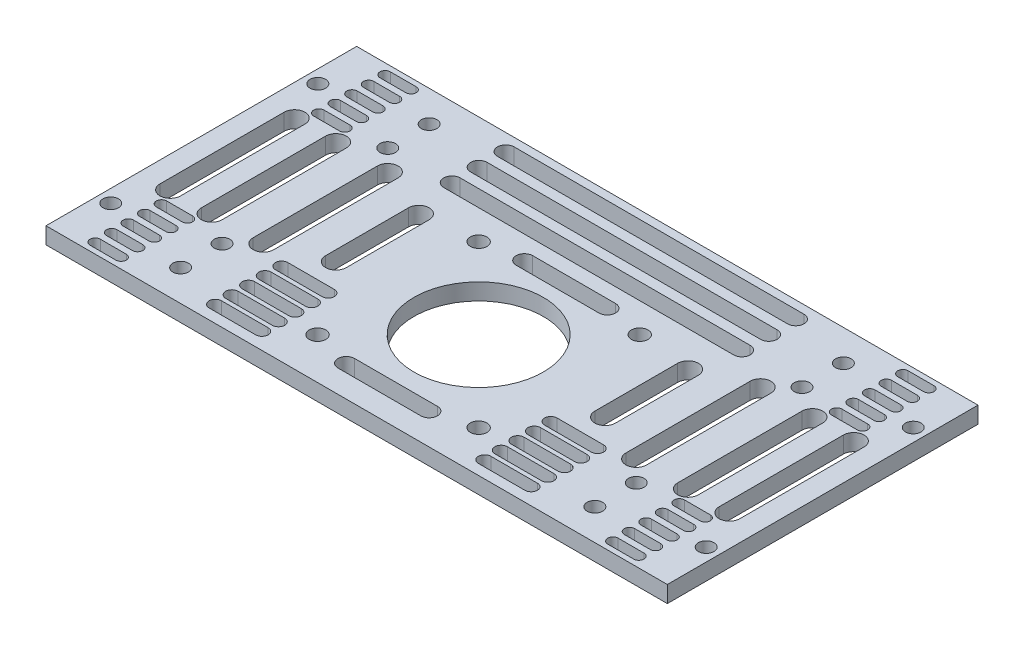
SolidWorks part; units mm, degrees
ref_plane "前视基准面" through (0, 0, 0) normal (0, 0, 1) x (1, 0, 0)
ref_plane "上视基准面" through (0, 0, 0) normal (0, 1, 0) x (1, 0, 0)
ref_plane "右视基准面" through (0, 0, 0) normal (1, 0, 0) x (0, 0, -1)
other "Configuration Table"
sketch "草图1" plane through (0, 0, 0) normal (0, 1, 0) x (1, 0, 0)
  line L0 (0, 30) -> (0, -30) construction
  line L1 (-60, 30) -> (60, 30)
  line L2 (-60, 30) -> (-60, -30)
  line L3 (-60, -30) -> (60, -30)
  line L4 (60, 30) -> (60, -30)
  line L6 (-60, 0) -> (60, 0) construction
  dimension "D1" = 60
  dimension "D2" = 120
extrude "凸台-拉伸1" add sketch "草图1" along normal blind 3.2
sketch "草图2" plane through (0, 3.2, 0) normal (0, 1, 0) x (1, 0, 0)
  line L0 (0, 0) -> (0, -30) construction
  line L1 (-60, -30) -> (60, -30) construction
  line L2 (0, 0) -> (0, 30) construction
  line L3 (60, 30) -> (-60, 30) construction
  line L4 (-15.5563, -22) -> (15.5563, -22) construction
  line L5 (0, -6.4437) -> (0, -22) construction
  line L6 (-60, 0) -> (60, 0) construction
  line L7 (-60, 30) -> (-60, -30) construction
  line L8 (60, -30) -> (60, 30) construction
  line L9 (-57.5, 30) -> (-57.5, -30) construction
  line L10 (-60, -20) -> (60, -20) construction
  line L11 (-60, 20) -> (60, 20) construction
  circle A0 centre (0, -6.4437) radius 12.5
  circle A1 centre (15.5563, -22) radius 1.6
  circle A2 centre (15.5563, 9.1127) radius 1.6
  circle A3 centre (-15.5563, 9.1127) radius 1.6
  circle A4 centre (-15.5563, -22) radius 1.6
  circle A5 centre (-57.5, 20) radius 1.5
  circle A6 centre (-57.5, -20) radius 1.5
  circle A7 centre (57.5, -20) radius 1.5
  circle A8 centre (57.5, 20) radius 1.5
  circle A9 centre (-40, -24) radius 1.5
  circle A10 centre (-40, -16) radius 1.5
  circle A11 centre (-40, 24) radius 1.5
  circle A12 centre (-40, 16) radius 1.5
  circle A13 centre (40, -24) radius 1.5
  circle A14 centre (40, -16) radius 1.5
  circle A15 centre (40, 24) radius 1.5
  circle A16 centre (40, 16) radius 1.5
  point P43 (-77.007, -22.6558)
  point P44 (-45.3884, -20.927)
  point P45 (-45.7748, -18.8737)
  dimension "D1" = 25
  dimension "D2" = 3.2
  dimension "D6" = 3
  dimension "D7" = 3
  dimension "D12" = 3
  dimension "D3" = 22
  dimension "D5" = 8
  dimension "D8" = 20
  dimension "D9" = 20
  dimension "D10" = 2.5
  dimension "D11" = 20
  dimension "D13" = 20
  dimension "D14" = 4
  dimension "D4" = 4
extrude "切除-拉伸1" cut sketch "草图2" against normal up to surface (3.2 mm away) up to face at (0, 0, 0)
sketch "草图3" plane through (0, 3.2, 0) normal (0, 1, 0) x (1, 0, 0)
  line L0 (0, 30) -> (0, -30) construction
  line L1 (60, 30) -> (-60, 30) construction
  line L2 (-60, -30) -> (60, -30) construction
  line L3 (-60, 0) -> (60, 0) construction
  line L4 (-60, 30) -> (-60, -30) construction
  line L5 (60, -30) -> (60, 30) construction
  line L6 (-28, 26.8) -> (28, 26.8) construction
  line L7 (-28, 28.4) -> (28, 28.4)
  line L8 (-28, 25.2) -> (28, 25.2)
  line L9 (-28, 21.6) -> (28, 21.6) construction
  line L10 (-28, 23.2) -> (28, 23.2)
  line L11 (-28, 20) -> (28, 20)
  line L12 (-28, 16.4) -> (28, 16.4) construction
  line L13 (-28, 18) -> (28, 18)
  line L14 (-28, 14.8) -> (28, 14.8)
  line L15 (-8, 10.4) -> (8, 10.4) construction
  line L16 (-8, 12) -> (8, 12)
  line L17 (-8, 8.8) -> (8, 8.8)
  line L18 (-8, -24) -> (8, -24) construction
  line L19 (-8, -22.4) -> (8, -22.4)
  line L20 (-8, -25.6) -> (8, -25.6)
  line L21 (-54, 12) -> (-54, -12) construction
  line L22 (-52, 12) -> (-52, -12)
  line L23 (-56, 12) -> (-56, -12)
  line L24 (-46, 12) -> (-46, -12) construction
  line L25 (-44, 12) -> (-44, -12)
  line L26 (-48, 12) -> (-48, -12)
  line L27 (-36, 12) -> (-36, -12) construction
  line L30 (-34, 12) -> (-34, -12)
  line L31 (-38, 12) -> (-38, -12)
  line L32 (54, 12) -> (54, -12) construction
  line L35 (-26, 8) -> (-26, -8) construction
  line L36 (-24, 8) -> (-24, -8)
  line L37 (-28, 8) -> (-28, -8)
  line L38 (52, 12) -> (52, -12)
  line L39 (56, 12) -> (56, -12)
  line L40 (46, 12) -> (46, -12) construction
  line L41 (44, 12) -> (44, -12)
  line L42 (48, 12) -> (48, -12)
  line L43 (36, 12) -> (36, -12) construction
  line L44 (34, 12) -> (34, -12)
  line L45 (38, 12) -> (38, -12)
  line L46 (26, 8) -> (26, -8) construction
  line L47 (24, 8) -> (24, -8)
  line L48 (28, 8) -> (28, -8)
  line L49 (-26, 8) -> (-26, -30) construction
  line L50 (-30.5, -17.2) -> (-21.5, -17.2) construction
  line L51 (-30.5, -16) -> (-21.5, -16)
  line L52 (-30.5, -18.4) -> (-21.5, -18.4)
  line L53 (-30.5, -20.4) -> (-21.5, -20.4) construction
  line L54 (-30.5, -19.2) -> (-21.5, -19.2)
  line L55 (-30.5, -21.6) -> (-21.5, -21.6)
  line L56 (-30.5, -23.6) -> (-21.5, -23.6) construction
  line L57 (-30.5, -22.4) -> (-21.5, -22.4)
  line L58 (-30.5, -24.8) -> (-21.5, -24.8)
  line L59 (-30.5, -26.8) -> (-21.5, -26.8) construction
  line L60 (-30.5, -25.6) -> (-21.5, -25.6)
  line L61 (-30.5, -28) -> (-21.5, -28)
  line L62 (-52, -12) -> (-48, -12) construction
  line L63 (-50, -12) -> (-50, -30) construction
  line L64 (-52.5, -15.2) -> (-47.5, -15.2) construction
  line L67 (-52.5, -18.4) -> (-47.5, -18.4) construction
  line L70 (-52.5, -24.8) -> (-47.5, -24.8) construction
  line L73 (-52.5, -23.8) -> (-47.5, -23.8)
  line L76 (-52.5, -28) -> (-47.5, -28) construction
  line L77 (-52.5, -27) -> (-47.5, -27)
  line L78 (-52.5, -29) -> (-47.5, -29)
  line L79 (-52.5, -17.4) -> (-47.5, -17.4)
  line L80 (-52.5, -19.4) -> (-47.5, -19.4)
  line L81 (-30.5, -14) -> (-21.5, -14) construction
  line L82 (-30.5, -12.8) -> (-21.5, -12.8)
  line L83 (-30.5, -15.2) -> (-21.5, -15.2)
  line L84 (-52.5, -25.8) -> (-47.5, -25.8)
  line L85 (-52.5, -21.6) -> (-47.5, -21.6) construction
  line L86 (-52.5, -20.6) -> (-47.5, -20.6)
  line L87 (-52.5, -22.6) -> (-47.5, -22.6)
  line L88 (-52.5, -14.2) -> (-47.5, -14.2)
  line L89 (-52.5, -16.2) -> (-47.5, -16.2)
  line L90 (52.5, -15.2) -> (47.5, -15.2) construction
  line L91 (52.5, -14.2) -> (47.5, -14.2)
  line L92 (52.5, -16.2) -> (47.5, -16.2)
  line L93 (52.5, -18.4) -> (47.5, -18.4) construction
  line L94 (52.5, -17.4) -> (47.5, -17.4)
  line L95 (52.5, -19.4) -> (47.5, -19.4)
  line L96 (52.5, -21.6) -> (47.5, -21.6) construction
  line L97 (52.5, -20.6) -> (47.5, -20.6)
  line L98 (52.5, -22.6) -> (47.5, -22.6)
  line L99 (52.5, -24.8) -> (47.5, -24.8) construction
  line L100 (52.5, -23.8) -> (47.5, -23.8)
  line L101 (52.5, -25.8) -> (47.5, -25.8)
  line L102 (52.5, -28) -> (47.5, -28) construction
  line L103 (52.5, -27) -> (47.5, -27)
  line L104 (52.5, -29) -> (47.5, -29)
  line L105 (30.5, -26.8) -> (21.5, -26.8) construction
  line L106 (30.5, -25.6) -> (21.5, -25.6)
  line L107 (30.5, -28) -> (21.5, -28)
  line L108 (30.5, -23.6) -> (21.5, -23.6) construction
  line L109 (30.5, -22.4) -> (21.5, -22.4)
  line L110 (30.5, -24.8) -> (21.5, -24.8)
  line L111 (30.5, -20.4) -> (21.5, -20.4) construction
  line L112 (30.5, -19.2) -> (21.5, -19.2)
  line L113 (30.5, -21.6) -> (21.5, -21.6)
  line L114 (30.5, -17.2) -> (21.5, -17.2) construction
  line L115 (30.5, -16) -> (21.5, -16)
  line L116 (30.5, -18.4) -> (21.5, -18.4)
  line L117 (30.5, -14) -> (21.5, -14) construction
  line L118 (30.5, -12.8) -> (21.5, -12.8)
  line L119 (30.5, -15.2) -> (21.5, -15.2)
  line L120 (-52.5, 15.2) -> (-47.5, 15.2) construction
  line L121 (-52.5, 14.2) -> (-47.5, 14.2)
  line L122 (-52.5, 16.2) -> (-47.5, 16.2)
  line L123 (-52.5, 18.4) -> (-47.5, 18.4) construction
  line L124 (-52.5, 17.4) -> (-47.5, 17.4)
  line L125 (-52.5, 19.4) -> (-47.5, 19.4)
  line L126 (-52.5, 21.6) -> (-47.5, 21.6) construction
  line L127 (-52.5, 20.6) -> (-47.5, 20.6)
  line L128 (-52.5, 22.6) -> (-47.5, 22.6)
  line L129 (-52.5, 24.8) -> (-47.5, 24.8) construction
  line L130 (-52.5, 23.8) -> (-47.5, 23.8)
  line L131 (-52.5, 25.8) -> (-47.5, 25.8)
  line L132 (-52.5, 28) -> (-47.5, 28) construction
  line L133 (-52.5, 27) -> (-47.5, 27)
  line L134 (-52.5, 29) -> (-47.5, 29)
  line L135 (52.5, 15.2) -> (47.5, 15.2) construction
  line L136 (52.5, 14.2) -> (47.5, 14.2)
  line L137 (52.5, 16.2) -> (47.5, 16.2)
  line L138 (52.5, 18.4) -> (47.5, 18.4) construction
  line L139 (52.5, 17.4) -> (47.5, 17.4)
  line L140 (52.5, 19.4) -> (47.5, 19.4)
  line L141 (52.5, 21.6) -> (47.5, 21.6) construction
  line L142 (52.5, 20.6) -> (47.5, 20.6)
  line L143 (52.5, 22.6) -> (47.5, 22.6)
  line L144 (52.5, 24.8) -> (47.5, 24.8) construction
  line L145 (52.5, 23.8) -> (47.5, 23.8)
  line L146 (52.5, 25.8) -> (47.5, 25.8)
  line L147 (52.5, 28) -> (47.5, 28) construction
  line L148 (52.5, 27) -> (47.5, 27)
  line L149 (52.5, 29) -> (47.5, 29)
  arc A0 (-28, 28.4) -> (-28, 25.2) centre (-28, 26.8) ccw
  arc A1 (28, 25.2) -> (28, 28.4) centre (28, 26.8) ccw
  arc A2 (-28, 23.2) -> (-28, 20) centre (-28, 21.6) ccw
  arc A3 (28, 20) -> (28, 23.2) centre (28, 21.6) ccw
  arc A4 (-28, 18) -> (-28, 14.8) centre (-28, 16.4) ccw
  arc A5 (28, 14.8) -> (28, 18) centre (28, 16.4) ccw
  arc A6 (-8, 12) -> (-8, 8.8) centre (-8, 10.4) ccw
  arc A7 (8, 8.8) -> (8, 12) centre (8, 10.4) ccw
  arc A8 (-8, -22.4) -> (-8, -25.6) centre (-8, -24) ccw
  arc A9 (8, -25.6) -> (8, -22.4) centre (8, -24) ccw
  arc A10 (-52, 12) -> (-56, 12) centre (-54, 12) ccw
  arc A11 (-56, -12) -> (-52, -12) centre (-54, -12) ccw
  arc A12 (-44, 12) -> (-48, 12) centre (-46, 12) ccw
  arc A13 (-48, -12) -> (-44, -12) centre (-46, -12) ccw
  arc A16 (-34, 12) -> (-38, 12) centre (-36, 12) ccw
  arc A17 (-38, -12) -> (-34, -12) centre (-36, -12) ccw
  arc A20 (-24, 8) -> (-28, 8) centre (-26, 8) ccw
  arc A21 (-28, -8) -> (-24, -8) centre (-26, -8) ccw
  arc A22 (52, 12) -> (56, 12) centre (54, 12) cw
  arc A23 (56, -12) -> (52, -12) centre (54, -12) cw
  arc A24 (44, 12) -> (48, 12) centre (46, 12) cw
  arc A25 (48, -12) -> (44, -12) centre (46, -12) cw
  arc A26 (34, 12) -> (38, 12) centre (36, 12) cw
  arc A27 (38, -12) -> (34, -12) centre (36, -12) cw
  arc A28 (24, 8) -> (28, 8) centre (26, 8) cw
  arc A29 (28, -8) -> (24, -8) centre (26, -8) cw
  arc A30 (-30.5, -16) -> (-30.5, -18.4) centre (-30.5, -17.2) ccw
  arc A31 (-21.5, -18.4) -> (-21.5, -16) centre (-21.5, -17.2) ccw
  arc A32 (-30.5, -19.2) -> (-30.5, -21.6) centre (-30.5, -20.4) ccw
  arc A33 (-21.5, -21.6) -> (-21.5, -19.2) centre (-21.5, -20.4) ccw
  arc A34 (-30.5, -22.4) -> (-30.5, -24.8) centre (-30.5, -23.6) ccw
  arc A35 (-21.5, -24.8) -> (-21.5, -22.4) centre (-21.5, -23.6) ccw
  arc A36 (-30.5, -25.6) -> (-30.5, -28) centre (-30.5, -26.8) ccw
  arc A37 (-21.5, -28) -> (-21.5, -25.6) centre (-21.5, -26.8) ccw
  arc A46 (-52.5, -27) -> (-52.5, -29) centre (-52.5, -28) ccw
  arc A47 (-47.5, -29) -> (-47.5, -27) centre (-47.5, -28) ccw
  arc A48 (-52.5, -17.4) -> (-52.5, -19.4) centre (-52.5, -18.4) ccw
  arc A49 (-47.5, -19.4) -> (-47.5, -17.4) centre (-47.5, -18.4) ccw
  arc A50 (-30.5, -12.8) -> (-30.5, -15.2) centre (-30.5, -14) ccw
  arc A51 (-21.5, -15.2) -> (-21.5, -12.8) centre (-21.5, -14) ccw
  arc A52 (-52.5, -23.8) -> (-52.5, -25.8) centre (-52.5, -24.8) ccw
  arc A53 (-47.5, -25.8) -> (-47.5, -23.8) centre (-47.5, -24.8) ccw
  arc A54 (-52.5, -20.6) -> (-52.5, -22.6) centre (-52.5, -21.6) ccw
  arc A55 (-47.5, -22.6) -> (-47.5, -20.6) centre (-47.5, -21.6) ccw
  arc A56 (-52.5, -14.2) -> (-52.5, -16.2) centre (-52.5, -15.2) ccw
  arc A57 (-47.5, -16.2) -> (-47.5, -14.2) centre (-47.5, -15.2) ccw
  arc A58 (52.5, -14.2) -> (52.5, -16.2) centre (52.5, -15.2) cw
  arc A59 (47.5, -16.2) -> (47.5, -14.2) centre (47.5, -15.2) cw
  arc A60 (52.5, -17.4) -> (52.5, -19.4) centre (52.5, -18.4) cw
  arc A61 (47.5, -19.4) -> (47.5, -17.4) centre (47.5, -18.4) cw
  arc A62 (52.5, -20.6) -> (52.5, -22.6) centre (52.5, -21.6) cw
  arc A63 (47.5, -22.6) -> (47.5, -20.6) centre (47.5, -21.6) cw
  arc A64 (52.5, -23.8) -> (52.5, -25.8) centre (52.5, -24.8) cw
  arc A65 (47.5, -25.8) -> (47.5, -23.8) centre (47.5, -24.8) cw
  arc A66 (52.5, -27) -> (52.5, -29) centre (52.5, -28) cw
  arc A67 (47.5, -29) -> (47.5, -27) centre (47.5, -28) cw
  arc A68 (30.5, -25.6) -> (30.5, -28) centre (30.5, -26.8) cw
  arc A69 (21.5, -28) -> (21.5, -25.6) centre (21.5, -26.8) cw
  arc A70 (30.5, -22.4) -> (30.5, -24.8) centre (30.5, -23.6) cw
  arc A71 (21.5, -24.8) -> (21.5, -22.4) centre (21.5, -23.6) cw
  arc A72 (30.5, -19.2) -> (30.5, -21.6) centre (30.5, -20.4) cw
  arc A73 (21.5, -21.6) -> (21.5, -19.2) centre (21.5, -20.4) cw
  arc A74 (30.5, -16) -> (30.5, -18.4) centre (30.5, -17.2) cw
  arc A75 (21.5, -18.4) -> (21.5, -16) centre (21.5, -17.2) cw
  arc A76 (30.5, -12.8) -> (30.5, -15.2) centre (30.5, -14) cw
  arc A77 (21.5, -15.2) -> (21.5, -12.8) centre (21.5, -14) cw
  arc A78 (-52.5, 14.2) -> (-52.5, 16.2) centre (-52.5, 15.2) cw
  arc A79 (-47.5, 16.2) -> (-47.5, 14.2) centre (-47.5, 15.2) cw
  arc A80 (-52.5, 17.4) -> (-52.5, 19.4) centre (-52.5, 18.4) cw
  arc A81 (-47.5, 19.4) -> (-47.5, 17.4) centre (-47.5, 18.4) cw
  arc A82 (-52.5, 20.6) -> (-52.5, 22.6) centre (-52.5, 21.6) cw
  arc A83 (-47.5, 22.6) -> (-47.5, 20.6) centre (-47.5, 21.6) cw
  arc A84 (-52.5, 23.8) -> (-52.5, 25.8) centre (-52.5, 24.8) cw
  arc A85 (-47.5, 25.8) -> (-47.5, 23.8) centre (-47.5, 24.8) cw
  arc A86 (-52.5, 27) -> (-52.5, 29) centre (-52.5, 28) cw
  arc A87 (-47.5, 29) -> (-47.5, 27) centre (-47.5, 28) cw
  arc A88 (52.5, 14.2) -> (52.5, 16.2) centre (52.5, 15.2) ccw
  arc A89 (47.5, 16.2) -> (47.5, 14.2) centre (47.5, 15.2) ccw
  arc A90 (52.5, 17.4) -> (52.5, 19.4) centre (52.5, 18.4) ccw
  arc A91 (47.5, 19.4) -> (47.5, 17.4) centre (47.5, 18.4) ccw
  arc A92 (52.5, 20.6) -> (52.5, 22.6) centre (52.5, 21.6) ccw
  arc A93 (47.5, 22.6) -> (47.5, 20.6) centre (47.5, 21.6) ccw
  arc A94 (52.5, 23.8) -> (52.5, 25.8) centre (52.5, 24.8) ccw
  arc A95 (47.5, 25.8) -> (47.5, 23.8) centre (47.5, 24.8) ccw
  arc A96 (52.5, 27) -> (52.5, 29) centre (52.5, 28) ccw
  arc A97 (47.5, 29) -> (47.5, 27) centre (47.5, 28) ccw
  point P14 (0, 26.8)
  point P20 (0, 21.6)
  point P27 (0, 16.4)
  point P34 (0, 10.4)
  point P41 (0, -24)
  point P49 (-54, 0)
  point P56 (-46, 0)
  point P63 (-36, 0)
  point P70 (54, 0)
  point P76 (-26, 0)
  point P84 (46, 0)
  point P91 (36, 0)
  point P98 (26, 0)
  point P107 (-26, -17.2)
  point P113 (-26, -20.4)
  point P120 (-26, -23.6)
  point P127 (-26, -26.8)
  point P139 (-50, -15.2)
  point P146 (-50, -18.4)
  point P153 (-50, -24.8)
  point P160 (-50, -21.6)
  point P166 (-50, -28)
  point P172 (0, 0)
  point P175 (-26, -14)
  point P180 (0, 0)
  point P181 (0, 0)
  point P182 (0, 0)
  point P185 (50, -15.2)
  point P192 (50, -18.4)
  point P199 (50, -21.6)
  point P206 (50, -24.8)
  point P213 (50, -28)
  point P220 (26, -26.8)
  point P227 (26, -23.6)
  point P234 (26, -20.4)
  point P241 (26, -17.2)
  point P248 (26, -14)
  point P255 (-50, 15.2)
  point P262 (-50, 18.4)
  point P269 (-50, 21.6)
  point P276 (-50, 24.8)
  point P283 (-50, 28)
  point P290 (50, 15.2)
  point P297 (50, 18.4)
  point P304 (50, 21.6)
  point P311 (50, 24.8)
  point P318 (50, 28)
  dimension "D53" = 2
  dimension "D57" = 5
  dimension "D1" = 56
  dimension "D2" = 1.6
  dimension "D3" = 1.6
  dimension "D4" = 56
  dimension "D5" = 1.6
  dimension "D6" = 56
  dimension "D7" = 16
  dimension "D8" = 1.6
  dimension "D9" = 16
  dimension "D10" = 1.6
  dimension "D11" = 3.2
  dimension "D12" = 5.2
  dimension "D13" = 5.2
  dimension "D14" = 6
  dimension "D15" = 6
  dimension "D16" = 24
  dimension "D17" = 24
  dimension "D18" = 24
  dimension "D19" = 2
  dimension "D20" = 2
  dimension "D21" = 2
  dimension "D22" = 16
  dimension "D23" = 2
  dimension "D24" = 6
  dimension "D25" = 8
  dimension "D26" = 10
  dimension "D27" = 10
  dimension "D28" = 1
  dimension "D29" = 1
  dimension "D30" = 1
  dimension "D31" = 5
  dimension "D32" = 9
  dimension "D33" = 9
  dimension "D34" = 9
  dimension "D35" = 9
  dimension "D36" = 3.2
  dimension "D37" = 1.2
  dimension "D38" = 1.2
  dimension "D39" = 1.2
  dimension "D40" = 1.2
  dimension "D41" = 3.2
  dimension "D42" = 3.2
  dimension "D43" = 3.2
  dimension "D44" = 1
  dimension "D45" = 5
  dimension "D46" = 3.2
  dimension "D47" = 3.2
  dimension "D48" = 1
  dimension "D49" = 5
  dimension "D50" = 1.2
  dimension "D51" = 9
  dimension "D52" = 3.2
  dimension "D54" = 3.2
  dimension "D55" = 3.2
  dimension "D56" = 5
extrude "切除-拉伸2" cut sketch "草图3" against normal up to surface (3.2 mm away) up to face at (57.5, 0, -18.5)
